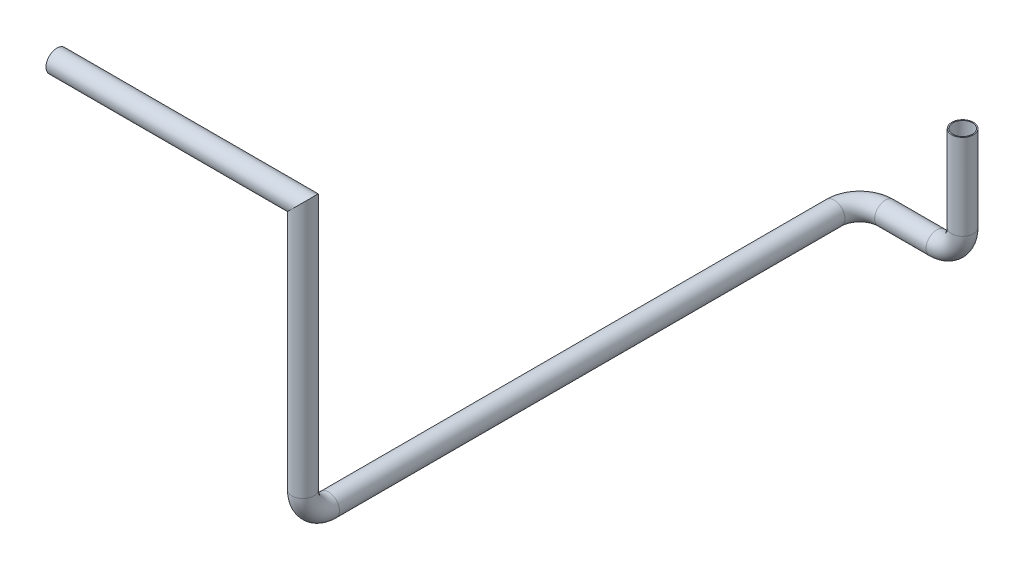
SolidWorks part; units mm, degrees
ref_plane "Alzado" through (0, 0, 0) normal (0, 0, 1) x (1, 0, 0)
ref_plane "Planta" through (0, 0, 0) normal (0, 1, 0) x (1, 0, 0)
ref_plane "Vista lateral" through (0, 0, 0) normal (1, 0, 0) x (0, 0, -1)
sketch "Croquis1" plane through (0, 0, 0) normal (0, 1, 0) x (1, 0, 0)
  circle A0 centre (0, 0) radius 12.7
  circle A1 centre (0, 0) radius 11.5
  dimension "D1" = 25.4
  dimension "D2" = 23
extrude "Saliente-Extruir1" add sketch "Croquis1" against normal blind 10
sketch3d "Croquis3D1"
  line L0 (0, -10, 0) -> (0, -100, 0)
  line L1 (0, -10, 0) -> (0, 0, 0) construction
  line L2 (-30, -130, 0) -> (-90, -130, 0)
  line L3 (-120, -130, 30) -> (-120, -130, 620)
  line L4 (-120, -100, 650) -> (-120, 190, 650)
  line L5 (-120, 190, 650) -> (-407.1138, 190, 650)
  arc A3 (-120, -130, 620) -> (-120, -100, 650) centre (-120, -100, 620) ccw
  arc A4 (-90, -130, 0) -> (-120, -130, 30) centre (-90, -130, 30) ccw
  arc A5 (0, -100, 0) -> (-30, -130, 0) centre (-30, -100, 0) ccw
  point P12 (230, 220, 1250)
  point P16 (230, 220, 650)
  point P20 (-120, 220, 650)
  point P24 (-120, -130, 650)
  point P25 (-150, -100, 620)
  point P28 (-120, -130, 0)
  point P29 (-90, -100, 30)
  point P32 (0, -130, 0)
  point P33 (-30, -100, -30)
  dimension "D1" = 120
  dimension "D2" = 120
  dimension "D3" = 650
  dimension "D4" = 350
  dimension "D5" = 350
  dimension "D6" = 600
sketch "Croquis2" plane through (0, -10, 0) normal (0, -1, 0) x (1, 0, 0)
  circle A0 centre (0, 0) radius 12.7
  circle A1 centre (0, 0) radius 11.5
sweep "Barrer1" add profiles "Croquis2" path "Croquis3D1"
